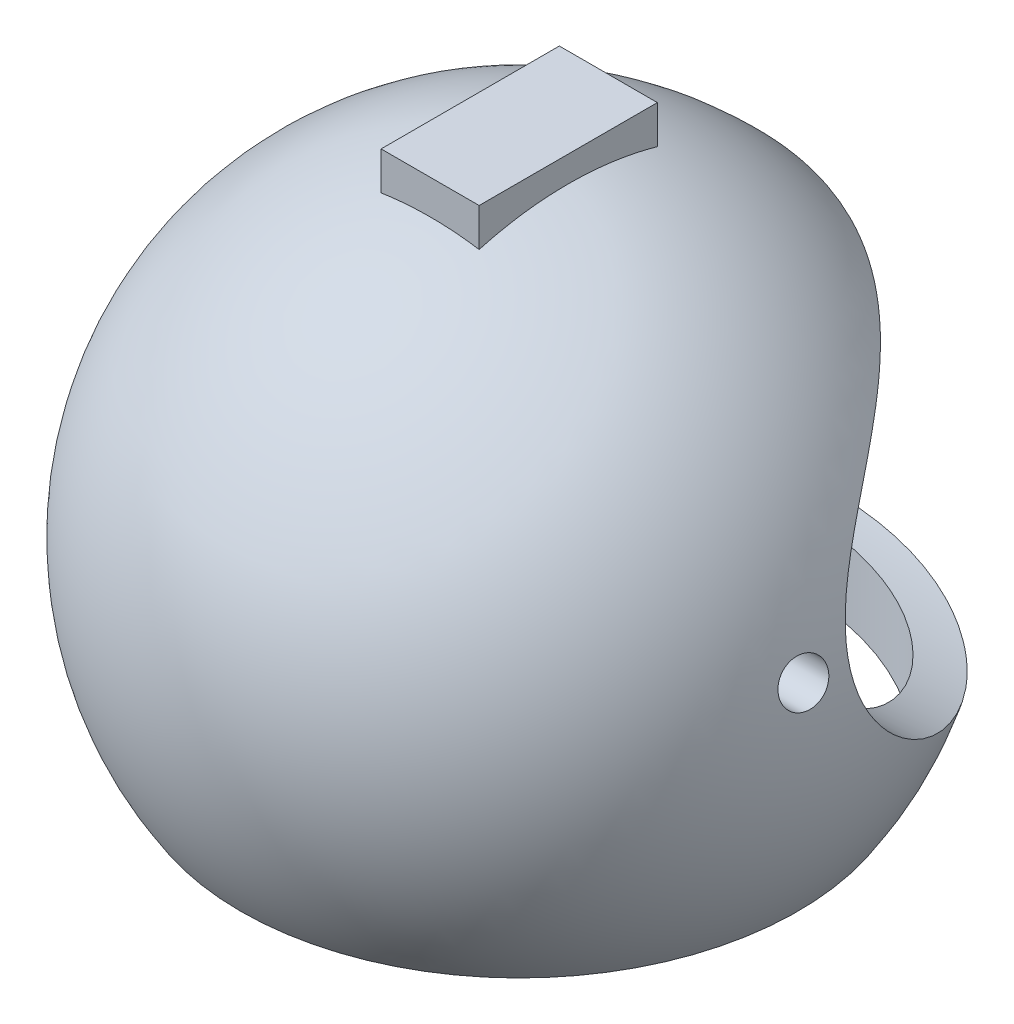
SolidWorks part; units mm, degrees
ref_plane "Front Plane" through (0, 0, 0) normal (0, 0, 1) x (1, 0, 0)
ref_plane "Top Plane" through (0, 0, 0) normal (0, 1, 0) x (1, 0, 0)
ref_plane "Right Plane" through (0, 0, 0) normal (1, 0, 0) x (0, 0, -1)
sketch "Sketch1" plane through (0, 0, 0) normal (0, 0, 1) x (1, 0, 0)
  line L0 (0, 124.6888) -> (0, -124.6888) construction
  line L1 (0, 75) -> (0, -75)
  arc A0 (0, 75) -> (0, -75) centre (0, 0) ccw
  dimension "D1" = 150
revolve "Revolve1" add sketch "Sketch1" angle 360 about L0
sketch "Sketch2" plane through (0, 0, 0) normal (0, 1, 0) x (1, 0, 0)
  circle A0 centre (0, 0) radius 62.5
  dimension "D1" = 125
extrude "Cut-Extrude2" cut sketch "Sketch2" against normal blind 75 and the other way blind 40
sketch "Sketch3" plane through (0, 0, 0) normal (1, 0, 0) x (0, 0, -1)
  arc A0 (70.282, -26.181) -> (53.697, 52.3606) centre (0, 0) ccw
  ellipse E0 centre (73.7156, 13.8205) end of major axis (0, 13.8205) minor radius 40.045 (53.697, 52.3606) -> (70.282, -26.181) ccw
  dimension "D1" = 13.8205
extrude "Cut-Extrude4" cut sketch "Sketch3" against normal through all both and the other way through all
ref_plane "Plane1" through (0, 75, 0) normal (0, 1, 0) x (1, 0, 0)
sketch "Sketch6" plane through (0, 75, 0) normal (0, 1, 0) x (1, 0, 0)
  line L1 (11, 20) -> (-11, 20)
  line L2 (11, 20) -> (11, -20)
  line L3 (11, -20) -> (-11, -20)
  line L4 (-11, 20) -> (-11, -20)
  line L5 (11, 20) -> (-11, -20) construction
  line L6 (11, -20) -> (-11, 20) construction
  point P0 (0, 0)
  dimension "D1" = 22
  dimension "D2" = 40
extrude "Boss-Extrude1" add sketch "Sketch6" along normal mid plane 10
sketch "Sketch7" plane through (0, 0, 0) normal (0, 0, 1) x (1, 0, 0)
  line L0 (-10.8, 80) -> (-10.8, 71.4728)
  line L1 (-11, 80) -> (11, 80) construction
  line L2 (-11, 80) -> (-11, 71.4423) construction
  line L3 (-10.6, 80) -> (-10.6, 71.4966)
  line L4 (-10.4, 80) -> (-10.4, 71.526)
  line L5 (-10.2, 80) -> (-10.2, 71.5548)
  line L6 (-10, 80) -> (-10, 71.583)
  line L7 (-9.8, 80) -> (-9.8, 71.6)
  line L8 (-9.6, 80) -> (-9.6, 71.6377)
  line L9 (-9.4, 80) -> (-9.4, 71.6643)
  line L10 (-9.2, 80) -> (-9.2, 71.6902)
  line L11 (-9, 80) -> (-9, 71.7156)
  line L12 (-8.8, 80) -> (-8.8, 71.7404)
  line L13 (-8.6, 80) -> (-8.6, 71.7647)
  line L14 (-8.4, 80) -> (-8.4, 71.7883)
  line L15 (-8.2, 80) -> (-8.2, 71.8115)
  line L16 (-8, 80) -> (-8, 71.834)
  line L17 (-7.8, 80) -> (-7.8, 71.856)
  line L18 (-7.6, 80) -> (-7.6, 71.8774)
  line L19 (-7.4, 80) -> (-7.4, 71.8983)
  line L20 (-7.2, 80) -> (-7.2, 71.9186)
  line L21 (-7, 80) -> (-7, 71.9383)
  line L22 (-6.8, 80) -> (-6.8, 71.9575)
  line L23 (-6.6, 80) -> (-6.6, 71.9761)
  line L24 (-6.4, 80) -> (-6.4, 71.9942)
  line L25 (-6.2, 80) -> (-6.2, 72.0117)
  line L26 (-6, 80) -> (-6, 72.0286)
  line L27 (-5.8, 80) -> (-5.8, 72.045)
  line L28 (-5.6, 80) -> (-5.6, 72.0608)
  line L29 (-5.4, 80) -> (-5.4, 72.0761)
  line L30 (-5.2, 80) -> (-5.2, 72.0908)
  line L31 (-5, 80) -> (-5, 72.105)
  line L32 (-4.8, 80) -> (-4.8, 72.1185)
  line L33 (-4.6, 80) -> (-4.6, 72.1316)
  line L34 (-4.4, 80) -> (-4.4, 72.1441)
  line L35 (-4.2, 80) -> (-4.2, 72.156)
  line L36 (-4, 80) -> (-4, 72.1673)
  line L37 (-3.8, 80) -> (-3.8, 72.1781)
  line L38 (-3.6, 80) -> (-3.6, 72.1884)
  line L39 (-3.4, 80) -> (-3.4, 72.1981)
  line L40 (-3.2, 80) -> (-3.2, 72.2072)
  line L41 (-3, 80) -> (-3, 72.2158)
  line L42 (-2.8, 80) -> (-2.8, 72.2239)
  line L43 (-2.6, 80) -> (-2.6, 72.2313)
  line L44 (-2.4, 80) -> (-2.4, 72.2383)
  line L45 (-2.2, 80) -> (-2.2, 72.2446)
  line L46 (-2, 80) -> (-2, 72.2504)
  line L47 (-1.8, 80) -> (-1.8, 72.2557)
  line L48 (-1.6, 80) -> (-1.6, 72.2604)
  line L49 (-1.4, 80) -> (-1.4, 72.2645)
  line L50 (-1.2, 80) -> (-1.2, 72.2681)
  line L51 (-1, 80) -> (-1, 72.2712)
  line L52 (-0.8, 80) -> (-0.8, 72.2737)
  line L53 (-0.6, 80) -> (-0.6, 72.2756)
  line L54 (-0.4, 80) -> (-0.4, 72.277)
  line L55 (-0.2, 80) -> (-0.2, 72.2778)
  line L56 (0, 80) -> (0, 72.2781)
  line L57 (0.2, 80) -> (0.2, 72.2778)
  line L58 (0.4, 80) -> (0.4, 72.277)
  line L59 (0.6, 80) -> (0.6, 72.2756)
  line L60 (0.8, 80) -> (0.8, 72.2737)
  line L61 (1, 80) -> (1, 72.2712)
  line L62 (1.2, 80) -> (1.2, 72.2681)
  line L63 (1.4, 80) -> (1.4, 72.2645)
  line L64 (1.6, 80) -> (1.6, 72.2604)
  line L65 (1.8, 80) -> (1.8, 72.2557)
  line L66 (2, 80) -> (2, 72.2504)
  line L67 (2.2, 80) -> (2.2, 72.2446)
  line L68 (2.4, 80) -> (2.4, 72.2383)
  line L69 (2.6, 80) -> (2.6, 72.2313)
  line L70 (2.8, 80) -> (2.8, 72.2239)
  line L71 (3, 80) -> (3, 72.2158)
  line L72 (3.2, 80) -> (3.2, 72.2072)
  line L73 (3.4, 80) -> (3.4, 72.1981)
  line L74 (3.6, 80) -> (3.6, 72.1884)
  line L75 (3.8, 80) -> (3.8, 72.1781)
  line L76 (4, 80) -> (4, 72.1673)
  line L77 (4.2, 80) -> (4.2, 72.156)
  line L78 (4.4, 80) -> (4.4, 72.1441)
  line L79 (4.6, 80) -> (4.6, 72.1316)
  line L80 (4.8, 80) -> (4.8, 72.1185)
  line L81 (5, 80) -> (5, 72.105)
  line L82 (5.2, 80) -> (5.2, 72.0908)
  line L83 (5.4, 80) -> (5.4, 72.0761)
  line L84 (5.6, 80) -> (5.6, 72.0608)
  line L85 (5.8, 80) -> (5.8, 72.045)
  line L86 (6, 80) -> (6, 72.0286)
  line L87 (6.2, 80) -> (6.2, 72.0117)
  line L88 (6.4, 80) -> (6.4, 71.9942)
  line L89 (6.6, 80) -> (6.6, 71.9761)
  line L90 (6.8, 80) -> (6.8, 71.9575)
  line L91 (7, 80) -> (7, 71.9383)
  line L92 (7.2, 80) -> (7.2, 71.9186)
  line L93 (7.4, 80) -> (7.4, 71.8983)
  line L94 (7.6, 80) -> (7.6, 71.8774)
  line L95 (7.8, 80) -> (7.8, 71.856)
  line L96 (8, 80) -> (8, 71.834)
  line L97 (8.2, 80) -> (8.2, 71.8115)
  line L98 (8.4, 80) -> (8.4, 71.7883)
  line L99 (8.6, 80) -> (8.6, 71.7647)
  line L100 (8.8, 80) -> (8.8, 71.7404)
  line L101 (9, 80) -> (9, 71.7156)
  line L102 (9.2, 80) -> (9.2, 71.6902)
  line L103 (9.4, 80) -> (9.4, 71.6643)
  line L104 (9.6, 80) -> (9.6, 71.6377)
  line L105 (9.8, 80) -> (9.8, 71.6106)
  line L106 (10, 80) -> (10, 71.583)
  line L107 (10.2, 80) -> (10.2, 71.5548)
  line L108 (10.4, 80) -> (10.4, 71.526)
  line L109 (10.6, 80) -> (10.6, 71.4966)
  line L110 (10.8, 80) -> (10.8, 71.4728)
  line L111 (-10.9, 80) -> (-10.9, 71.4728)
  line L112 (-10.7, 80) -> (-10.7, 71.4817)
  line L113 (-10.5, 80) -> (-10.5, 71.5114)
  line L114 (-10.3, 80) -> (-10.3, 71.5404)
  line L115 (-10.1, 80) -> (-10.1, 71.569)
  line L116 (-9.9, 80) -> (-9.9, 71.5969)
  line L117 (-9.7, 80) -> (-9.7, 71.6243)
  line L118 (-9.5, 80) -> (-9.5, 71.6511)
  line L119 (-9.3, 80) -> (-9.3, 71.6773)
  line L120 (-9.1, 80) -> (-9.1, 71.6997)
  line L121 (-8.9, 80) -> (-8.9, 71.7281)
  line L122 (-8.7, 80) -> (-8.7, 71.7526)
  line L123 (-8.5, 80) -> (-8.5, 71.7766)
  line L124 (-8.3, 80) -> (-8.3, 71.8)
  line L125 (-8.1, 80) -> (-8.1, 71.8228)
  line L126 (-7.9, 80) -> (-7.9, 71.8451)
  line L127 (-7.7, 80) -> (-7.7, 71.8668)
  line L128 (-7.5, 80) -> (-7.5, 71.8879)
  line L129 (-7.3, 80) -> (-7.3, 71.8997)
  line L130 (-7.1, 80) -> (-7.1, 71.9285)
  line L131 (-6.9, 80) -> (-6.9, 71.948)
  line L132 (-6.7, 80) -> (-6.7, 71.9669)
  line L133 (-6.5, 80) -> (-6.5, 71.9852)
  line L134 (-6.3, 80) -> (-6.3, 72.003)
  line L135 (-6.1, 80) -> (-6.1, 72.0202)
  line L136 (-5.9, 80) -> (-5.9, 72.0369)
  line L137 (-5.7, 80) -> (-5.7, 72.053)
  line L138 (-5.5, 80) -> (-5.5, 72.0685)
  line L139 (-5.3, 80) -> (-5.3, 72.0835)
  line L140 (-5.1, 80) -> (-5.1, 72.098)
  line L141 (-4.9, 80) -> (-4.9, 72.1118)
  line L142 (-4.7, 80) -> (-4.7, 72.1251)
  line L143 (-4.5, 80) -> (-4.5, 72.1379)
  line L144 (-4.3, 80) -> (-4.3, 72.1501)
  line L145 (-4.1, 80) -> (-4.1, 72.1617)
  line L146 (-3.9, 80) -> (-3.9, 72.1728)
  line L147 (-3.7, 80) -> (-3.7, 72.1833)
  line L148 (-3.5, 80) -> (-3.5, 72.1933)
  line L149 (-3.3, 80) -> (-3.3, 72.2027)
  line L150 (-3.1, 80) -> (-3.1, 72.2116)
  line L151 (-2.9, 80) -> (-2.9, 72.2199)
  line L152 (-2.7, 80) -> (-2.7, 72.2277)
  line L153 (-2.5, 80) -> (-2.5, 72.2349)
  line L154 (-2.3, 80) -> (-2.3, 72.2415)
  line L155 (-2.1, 80) -> (-2.1, 72.2476)
  line L156 (-1.9, 80) -> (-1.9, 72.2531)
  line L157 (-1.7, 80) -> (-1.7, 72.2581)
  line L158 (-1.5, 80) -> (-1.5, 72.2625)
  line L159 (-1.3, 80) -> (-1.3, 72.2664)
  line L160 (-1.1, 80) -> (-1.1, 72.2697)
  line L161 (-0.9, 80) -> (-0.9, 72.2725)
  line L162 (-0.7, 80) -> (-0.7, 72.2747)
  line L163 (-0.5, 80) -> (-0.5, 72.2764)
  line L164 (-0.3, 80) -> (-0.3, 72.2775)
  line L165 (-0.1, 80) -> (-0.1, 72.278)
  line L166 (0.1, 80) -> (0.1, 72.278)
  line L167 (0.3, 80) -> (0.3, 72.2775)
  line L168 (0.5, 80) -> (0.5, 72.2764)
  line L169 (0.7, 80) -> (0.7, 72.2747)
  line L170 (0.9, 80) -> (0.9, 72.2725)
  line L171 (1.1, 80) -> (1.1, 72.2697)
  line L172 (1.3, 80) -> (1.3, 72.2664)
  line L173 (1.5, 80) -> (1.5, 72.2625)
  line L174 (1.7, 80) -> (1.7, 72.2581)
  line L175 (1.9, 80) -> (1.9, 72.2531)
  line L176 (2.1, 80) -> (2.1, 72.2476)
  line L177 (2.3, 80) -> (2.3, 72.2415)
  line L178 (2.5, 80) -> (2.5, 72.2349)
  line L179 (2.7, 80) -> (2.7, 72.2277)
  line L180 (2.9, 80) -> (2.9, 72.2199)
  line L181 (3.1, 80) -> (3.1, 72.2116)
  line L182 (3.3, 80) -> (3.3, 72.2)
  line L183 (3.5, 80) -> (3.5, 72.1933)
  line L184 (3.7, 80) -> (3.7, 72.1833)
  line L185 (3.9, 80) -> (3.9, 72.1728)
  line L186 (4.1, 80) -> (4.1, 72.1617)
  line L187 (4.3, 80) -> (4.3, 72.1501)
  line L188 (4.5, 80) -> (4.5, 72.1379)
  line L189 (4.7, 80) -> (4.7, 72.1251)
  line L190 (4.9, 80) -> (4.9, 72.1118)
  line L191 (5.1, 80) -> (5.1, 72.098)
  line L192 (5.3, 80) -> (5.3, 72.0835)
  line L193 (5.5, 80) -> (5.5, 72.0685)
  line L194 (5.7, 80) -> (5.7, 72.053)
  line L195 (5.9, 80) -> (5.9, 72.0369)
  line L196 (6.1, 80) -> (6.1, 72.0202)
  line L197 (6.3, 80) -> (6.3, 72)
  line L198 (6.5, 80) -> (6.5, 71.9852)
  line L199 (6.7, 80) -> (6.7, 71.9669)
  line L200 (6.9, 80) -> (6.9, 71.948)
  line L201 (7.1, 80) -> (7.1, 71.9285)
  line L202 (7.3, 80) -> (7.3, 71.9085)
  line L203 (7.5, 80) -> (7.5, 71.8879)
  line L204 (7.7, 80) -> (7.7, 71.8668)
  line L205 (7.9, 80) -> (7.9, 71.8451)
  line L206 (8.1, 80) -> (8.1, 71.8228)
  line L207 (8.3, 80) -> (8.3, 71.8)
  line L208 (8.5, 80) -> (8.5, 71.7766)
  line L209 (8.7, 80) -> (8.7, 71.7526)
  line L210 (8.9, 80) -> (8.9, 71.7281)
  line L211 (9.1, 80) -> (9.1, 71.703)
  line L212 (9.3, 80) -> (9.3, 71.6773)
  line L213 (9.5, 80) -> (9.5, 71.6511)
  line L214 (9.7, 80) -> (9.7, 71.6243)
  line L215 (9.9, 80) -> (9.9, 71.5969)
  line L216 (10.1, 80) -> (10.1, 71.569)
  line L217 (10.3, 80) -> (10.3, 71.5404)
  line L218 (10.5, 80) -> (10.5, 71.5114)
  line L219 (10.7, 80) -> (10.7, 71.4817)
  line L220 (-11, 79.8) -> (11, 79.8)
  line L221 (11, 80) -> (11, 71.4423) construction
  line L222 (-11, 79.6) -> (11, 79.6)
  line L223 (-11, 79.4) -> (11, 79.4)
  line L224 (-11, 79.2) -> (11, 79.2)
  line L225 (-11, 79) -> (11, 79)
  line L226 (-11, 78.8) -> (11, 78.8)
  line L227 (-11, 78.6) -> (11, 78.6)
  line L228 (-11, 78.4) -> (11, 78.4)
  line L229 (-11, 78.2) -> (11, 78.2)
  line L230 (-11, 78) -> (11, 78)
  line L231 (-11, 77.8) -> (11, 77.8)
  line L232 (-11, 77.6) -> (11, 77.6)
  line L233 (-11, 77.4) -> (11, 77.4)
  line L234 (-11, 77.2) -> (11, 77.2)
  line L235 (-11, 77) -> (11, 77)
  line L236 (-11, 76.8) -> (11, 76.8)
  line L237 (-11, 76.6) -> (11, 76.6)
  line L238 (-11, 76.4) -> (11, 76.4)
  line L239 (-11, 76.2) -> (11, 76.2)
  line L240 (-11, 76) -> (11, 76)
  line L241 (-11, 75.8) -> (11, 75.8)
  line L242 (-11, 75.6) -> (11, 75.6)
  line L243 (-11, 75.4) -> (11, 75.4)
  line L244 (-11, 75.2) -> (11, 75.2)
  line L245 (-11, 75) -> (11, 75)
  line L246 (-11, 74.8) -> (11, 74.8)
  line L247 (-11, 74.6) -> (11, 74.6)
  line L248 (-11, 74.4) -> (11, 74.4)
  line L249 (-11, 74.2) -> (11, 74.2)
  line L250 (-11, 74) -> (11, 74)
  line L251 (-11, 73.8) -> (11, 73.8)
  line L252 (-11, 73.6) -> (11, 73.6)
  line L253 (-11, 73.4) -> (11, 73.4)
  line L254 (-11, 73.2) -> (11, 73.2)
  line L255 (-11, 73) -> (11, 73)
  line L256 (-11, 72.8) -> (11, 72.8)
  line L257 (-11, 72.6) -> (11, 72.6)
  line L258 (-11, 72.4) -> (11, 72.4)
  line L259 (-11, 72.2) -> (-3.3593, 72.2)
  line L260 (-11, 72) -> (-6.3344, 72)
  line L261 (-11, 71.8) -> (-8.2997, 71.8)
  line L262 (-11, 71.6) -> (-9.8, 71.6)
  line L263 (11, 79.8997) -> (-11, 79.8997)
  line L264 (11, 79.6997) -> (-11, 79.6997)
  line L265 (11, 79.4997) -> (-11, 79.4997)
  line L266 (11, 79.2997) -> (-11, 79.2997)
  line L267 (11, 79.0997) -> (-11, 79.0997)
  line L268 (11, 78.8997) -> (-11, 78.8997)
  line L269 (11, 78.6997) -> (-11, 78.6997)
  line L270 (11, 78.4997) -> (-11, 78.4997)
  line L271 (11, 78.2997) -> (-11, 78.2997)
  line L272 (11, 78.0997) -> (-11, 78.0997)
  line L273 (11, 77.8997) -> (-11, 77.8997)
  line L274 (11, 77.6997) -> (-11, 77.6997)
  line L275 (11, 77.4997) -> (-11, 77.4997)
  line L276 (11, 77.2997) -> (-11, 77.2997)
  line L277 (11, 77.0997) -> (-11, 77.0997)
  line L278 (11, 76.8997) -> (-11, 76.8997)
  line L279 (11, 76.6997) -> (-11, 76.6997)
  line L280 (11, 76.4997) -> (-11, 76.4997)
  line L281 (11, 76.2997) -> (-11, 76.2997)
  line L282 (11, 76.0997) -> (-11, 76.0997)
  line L283 (11, 75.8997) -> (-11, 75.8997)
  line L284 (11, 75.6997) -> (-11, 75.6997)
  line L285 (11, 75.4997) -> (-11, 75.4997)
  line L286 (11, 75.2997) -> (-11, 75.2997)
  line L287 (11, 75.0997) -> (-11, 75.0997)
  line L288 (11, 74.8997) -> (-11, 74.8997)
  line L289 (11, 74.6997) -> (-11, 74.6997)
  line L290 (11, 74.4997) -> (-11, 74.4997)
  line L291 (11, 74.2997) -> (-11, 74.2997)
  line L292 (11, 74.0997) -> (-11, 74.0997)
  line L293 (11, 73.8997) -> (-11, 73.8997)
  line L294 (11, 73.6997) -> (-11, 73.6997)
  line L295 (11, 73.4997) -> (-11, 73.4997)
  line L296 (11, 73.2997) -> (-11, 73.2997)
  line L297 (11, 73.0997) -> (-11, 73.0997)
  line L298 (11, 72.8997) -> (-11, 72.8997)
  line L299 (11, 72.6997) -> (-11, 72.6997)
  line L300 (11, 72.4997) -> (-11, 72.4997)
  line L301 (11, 72.2997) -> (-11, 72.2997)
  line L302 (11, 72.0997) -> (5.0756, 72.0997)
  line L303 (11, 71.8997) -> (7.3866, 71.8997)
  line L304 (11, 71.6997) -> (9.1259, 71.6997)
  line L305 (-5.0756, 72.0997) -> (-11, 72.0997)
  line L306 (6.3, 72) -> (11, 72)
  line L307 (-9.1, 71.6997) -> (-11, 71.6997)
  line L308 (-11, 80) -> (-11, 71.4423)
  line L309 (3.3, 72.2) -> (11, 72.2)
  line L310 (-11, 80) -> (11, 80)
  line L311 (8.2997, 71.8) -> (11, 71.8)
  line L312 (11, 80) -> (11, 71.4423)
  line L320 (-7.3, 71.8997) -> (-11, 71.8997)
  line L406 (9.8775, 71.6) -> (11, 71.6)
  arc A0 (11, 71.4423) -> (-11, 71.4423) centre (0, 0) ccw construction
  arc A1 (10.7, 71.4817) -> (-10.7, 71.4817) centre (0, 0) ccw
  dimension "D1" = 0.2
  dimension "D3" = 0.1
  dimension "D5" = 0.2
  dimension "D7" = 0.0997
  dimension "D2" = 109
  dimension "D4" = 109
  dimension "D6" = 42
  dimension "D8" = 42
sketch "Sketch8" plane through (0, 0, 0) normal (1, 0, 0) x (0, 0, -1)
  circle A0 centre (-9.3312, 12.9501) radius 5
  dimension "D1" = 10
extrude "Cut-Extrude5" cut sketch "Sketch8" against normal through all both and the other way through all
